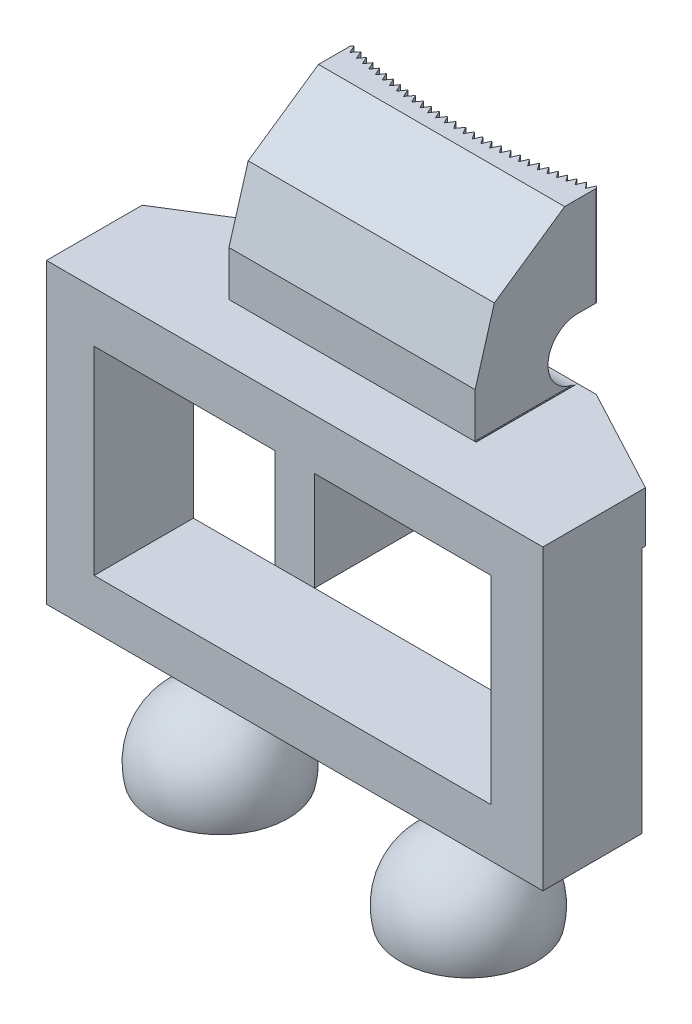
SolidWorks part; units mm, degrees
ref_plane "Front Plane" through (0, 0, 0) normal (0, 0, 1) x (1, 0, 0)
ref_plane "Top Plane" through (0, 0, 0) normal (0, 1, 0) x (1, 0, 0)
ref_plane "Right Plane" through (0, 0, 0) normal (1, 0, 0) x (0, 0, -1)
sketch "Sketch1" plane through (0, 0, 0) normal (0, 0, 1) x (1, 0, 0)
  line L5 (0, 0) -> (20, 0)
  line L6 (0, 0) -> (0, 10)
  line L7 (0, 10) -> (20, 10)
  line L8 (20, 0) -> (20, 10)
  line L9 (-2.3985, 12.5459) -> (22.6015, 12.5459)
  line L10 (-2.3985, 12.5459) -> (-2.3985, -2.4541)
  line L11 (-2.3985, -2.4541) -> (22.6015, -2.4541)
  line L12 (22.6015, 12.5459) -> (22.6015, -2.4541)
  dimension "D1" = 10
  dimension "D2" = 20
  dimension "D3" = 15
  dimension "D4" = 25
extrude "Boss-Extrude1" add sketch "Sketch1" along normal blind 5
sketch "Sketch2" plane through (0, -2.4541, 0) normal (0, -1, 0) x (1, 0, 0)
  line L3 (10.1015, 2.5) -> (10.1015, 0)
  line L4 (-2.3985, 0) -> (22.6015, 0) construction
  circle A0 centre (16.3515, 2.5) radius 0.5
  circle A1 centre (3.8515, 2.5) radius 0.5
  dimension "D1" = 1
extrude "Boss-Extrude2" add sketch "Sketch2" along normal blind 2 contours A1 | A0
ref_plane "Plane1" through (3.8515, 0, 0) normal (-1, 0, 0) x (0, 0, 1)
sketch "Sketch4" plane through (3.8515, 0, 0) normal (-1, 0, 0) x (0, 0, 1)
  line L1 (2, -4.4541) -> (3, -4.4541) construction
  line L2 (2.5, -4.4541) -> (2.5, -3.9541)
  line L4 (-0.4312, -8.0929) -> (-0.9159, -8.2167)
  arc A0 (2.5, -4.4541) -> (-0.4312, -8.0929) centre (2.5, -7.4541) ccw
  arc A1 (2.5, -3.9541) -> (-0.9159, -8.2167) centre (2.5, -7.4541) ccw
  dimension "D2" = 7
  dimension "D1" = 3
revolve "Revolve1" add sketch "Sketch4" angle 360 about L2
ref_plane "Plane2" through (10.1015, 0, 0) normal (-1, 0, 0) x (0, 0, 1)
mirror "Mirror1" about plane through (10.1015, 0, 0) normal (-1, 0, 0) of "Revolve1"
sketch "Sketch5" plane through (0, 10, 0) normal (0, -1, 0) x (1, 0, 0)
  line L9 (11.1015, 0) -> (11.1015, 5)
  line L10 (9.1015, 0) -> (9.1015, 5)
  line L11 (11.1015, 0) -> (9.1015, 0)
  line L12 (11.1015, 5) -> (9.1015, 5)
extrude "Boss-Extrude3" add sketch "Sketch5" along normal blind 5
sketch "Sketch6" plane through (0, 12.5459, 0) normal (0, 1, 0) x (1, 0, 0)
  line L0 (10.1015, 0) -> (10.1015, -5)
  line L1 (22.6015, 0) -> (-2.3985, 0) construction
  line L2 (22.6015, -5) -> (-2.3985, -5) construction
sketch "Sketch9" plane through (0, 12.5459, 0) normal (0, 1, 0) x (1, 0, 0)
  line L0 (22.6015, 0) -> (22.6015, 3)
  line L1 (22.6015, 3) -> (-2.3985, 3)
  line L2 (-2.3985, 3) -> (-2.3985, 0)
  line L3 (22.6015, 0) -> (-2.3985, 0)
  dimension "D1" = 3
  dimension "D2" = 25
extrude "Boss-Extrude6" add sketch "Sketch9" against normal blind 2.5458 contours L1 L2 L3 L0
sketch "Sketch10" plane through (-2.3985, 0, 0) normal (-1, 0, 0) x (0, 0, 1)
  line L3 (-3, 20.5459) -> (-3, 15.5459)
  line L4 (-3, 20.5459) -> (-3, 15.5459)
  line L5 (-3, 12.5459) -> (2.1099, 12.5459)
  line L6 (-3, 20.5459) -> (-2.3985, 20.5459)
  line L7 (-2.3985, 20.5459) -> (1.1419, 18.1122)
  line L9 (1.1419, 18.1122) -> (2.1099, 14.8124)
  line L10 (2.1099, 14.8124) -> (2.1099, 12.5459)
  arc A0 (-3, 12.5459) -> (-3, 15.5459) centre (-3.0614, 14.0459) ccw
  circle A1 centre (-2.1099, 12.5459) radius 12.9256
  dimension "D3" = 5
extrude "Boss-Extrude11" add sketch "Sketch10" against normal blind 25 contours L3 L6 L7 L9 L10 L5 A0
sketch "Sketch11" plane through (0, 20.5459, 0) normal (0, 1, 0) x (1, 0, 0)
  line L1 (22.6015, 6.37) -> (22.2185, 6.5835)
  line L2 (10.3551, 3.3672) -> (10.1015, 3.0172)
  line L5 (22.2065, 6.1451) -> (22.2185, 6.5835)
  line L6 (22.2065, 6.1451) -> (21.8398, 6.3643)
  line L7 (21.8398, 6.3643) -> (21.8398, 5.9448)
  line L8 (21.8398, 5.9448) -> (21.4709, 6.1653)
  line L9 (21.4709, 6.1653) -> (21.4709, 5.7513)
  line L10 (21.4709, 5.7513) -> (21.0903, 5.9787)
  line L11 (21.0903, 5.9787) -> (21.0903, 5.5597)
  line L12 (21.0903, 5.5597) -> (20.715, 5.784)
  line L13 (20.715, 5.784) -> (20.715, 5.3787)
  line L14 (20.715, 5.3787) -> (20.3402, 5.6027)
  line L15 (20.3402, 5.6027) -> (20.3402, 5.2056)
  line L16 (20.3402, 5.2056) -> (19.9698, 5.427)
  line L17 (19.9698, 5.427) -> (19.9698, 5.0419)
  line L18 (19.9698, 5.0419) -> (19.6095, 5.2572)
  line L19 (19.6095, 5.2572) -> (19.6095, 4.8895)
  line L20 (19.6095, 4.8895) -> (19.24, 5.1102)
  line L21 (19.24, 5.1102) -> (19.204, 4.7258)
  line L22 (19.204, 4.7258) -> (18.8434, 4.9413)
  line L23 (18.8434, 4.9413) -> (18.809, 4.5743)
  line L24 (18.809, 4.5743) -> (18.4829, 4.8336)
  line L25 (18.4829, 4.8336) -> (18.4343, 4.4377)
  line L26 (18.4343, 4.4377) -> (18.0993, 4.704)
  line L27 (18.0993, 4.704) -> (18.0296, 4.2976)
  line L28 (18.0296, 4.2976) -> (17.6859, 4.5708)
  line L29 (17.6859, 4.5708) -> (17.6366, 4.1691)
  line L30 (10.7776, 3.3845) -> (10.5576, 3.0172)
  line L31 (17.3643, 4.4686) -> (17.6366, 4.1691)
  line L32 (17.2415, 4.0471) -> (17.3643, 4.4686)
  line L33 (16.9499, 4.3385) -> (17.2415, 4.0471)
  line L34 (16.8302, 3.9276) -> (16.9499, 4.3385)
  line L35 (16.5619, 4.2228) -> (16.8302, 3.9276)
  line L36 (16.4454, 3.8228) -> (16.5619, 4.2228)
  line L37 (16.2053, 4.1025) -> (16.4454, 3.8228)
  line L38 (16.0354, 3.7184) -> (16.2053, 4.1025)
  line L39 (15.784, 4.0114) -> (16.0354, 3.7184)
  line L40 (15.6099, 3.6178) -> (15.784, 4.0114)
  line L41 (15.3975, 3.918) -> (15.6099, 3.6178)
  line L42 (15.2278, 3.5341) -> (15.3975, 3.918)
  line L43 (15.0053, 3.8485) -> (15.2278, 3.5341)
  line L44 (14.8308, 3.4538) -> (15.0053, 3.8485)
  line L45 (14.6014, 3.778) -> (14.8308, 3.4538)
  line L46 (14.4248, 3.3787) -> (14.6014, 3.778)
  line L47 (14.1908, 3.7095) -> (14.4248, 3.3787)
  line L48 (14.014, 3.3097) -> (14.1908, 3.7095)
  line L49 (13.772, 3.6518) -> (14.014, 3.3097)
  line L50 (13.5926, 3.2463) -> (13.772, 3.6518)
  line L51 (13.3535, 3.5843) -> (13.5926, 3.2463)
  line L52 (13.1797, 3.1912) -> (13.3535, 3.5843)
  line L53 (12.9374, 3.5337) -> (13.1797, 3.1912)
  line L54 (12.7646, 3.143) -> (12.9374, 3.5337)
  line L55 (12.7646, 3.143) -> (12.5017, 3.4939)
  line L56 (9.8479, 3.3672) -> (9.6181, 3.0172)
  line L57 (12.3122, 3.0985) -> (12.5017, 3.4939)
  line L58 (9.6181, 3.0172) -> (9.4255, 3.3845)
  line L59 (12.3122, 3.0985) -> (12.0558, 3.4541)
  line L60 (9.1771, 3.0172) -> (9.4255, 3.3845)
  line L61 (11.8591, 3.0622) -> (12.0558, 3.4541)
  line L62 (11.8591, 3.0622) -> (11.6199, 3.4161)
  line L63 (11.6199, 3.4161) -> (11.4421, 3.0362)
  line L64 (11.4421, 3.0362) -> (11.2014, 3.3922)
  line L65 (11.2014, 3.3922) -> (11.0259, 3.0172)
  line L66 (11.0259, 3.0172) -> (10.7776, 3.3845)
  line L67 (10.5576, 3.0172) -> (10.3551, 3.3672)
  line L68 (9.8479, 3.3672) -> (10.1015, 3.0172)
  line L69 (22.6015, 6.37) -> (22.6015, 3)
  line L70 (22.6015, 3) -> (-2.3985, 3)
  line L71 (10.1015, 2.75) -> (10.1015, -2.75) construction
  line L72 (9.0017, 3.3922) -> (9.1771, 3.0172)
  line L73 (8.761, 3.0362) -> (9.0017, 3.3922)
  line L74 (8.5832, 3.4161) -> (8.761, 3.0362)
  line L75 (8.3439, 3.0622) -> (8.5832, 3.4161)
  line L76 (8.3439, 3.0622) -> (8.1473, 3.4541)
  line L77 (7.8908, 3.0985) -> (8.1473, 3.4541)
  line L78 (7.8908, 3.0985) -> (7.7014, 3.4939)
  line L79 (7.4385, 3.143) -> (7.7014, 3.4939)
  line L80 (7.4385, 3.143) -> (7.2657, 3.5337)
  line L81 (7.2657, 3.5337) -> (7.0234, 3.1912)
  line L82 (7.0234, 3.1912) -> (6.8496, 3.5843)
  line L83 (6.8496, 3.5843) -> (6.6105, 3.2463)
  line L84 (6.6105, 3.2463) -> (6.4311, 3.6518)
  line L85 (6.4311, 3.6518) -> (6.1891, 3.3097)
  line L86 (6.1891, 3.3097) -> (6.0123, 3.7095)
  line L87 (6.0123, 3.7095) -> (5.7782, 3.3787)
  line L88 (5.7782, 3.3787) -> (5.6016, 3.778)
  line L89 (5.6016, 3.778) -> (5.3723, 3.4538)
  line L90 (5.3723, 3.4538) -> (5.1977, 3.8485)
  line L91 (5.1977, 3.8485) -> (4.9753, 3.5341)
  line L92 (4.9753, 3.5341) -> (4.8055, 3.918)
  line L93 (4.8055, 3.918) -> (4.5931, 3.6178)
  line L94 (4.5931, 3.6178) -> (4.419, 4.0114)
  line L95 (4.419, 4.0114) -> (4.1676, 3.7184)
  line L96 (4.1676, 3.7184) -> (3.9977, 4.1025)
  line L97 (3.9977, 4.1025) -> (3.7577, 3.8228)
  line L98 (3.7577, 3.8228) -> (3.6412, 4.2228)
  line L99 (3.6412, 4.2228) -> (3.3728, 3.9276)
  line L100 (3.3728, 3.9276) -> (3.2531, 4.3385)
  line L101 (3.2531, 4.3385) -> (2.9615, 4.0471)
  line L102 (2.9615, 4.0471) -> (2.8387, 4.4686)
  line L103 (2.8387, 4.4686) -> (2.5665, 4.1691)
  line L104 (2.5172, 4.5708) -> (2.5665, 4.1691)
  line L105 (2.1735, 4.2976) -> (2.5172, 4.5708)
  line L106 (2.1038, 4.704) -> (2.1735, 4.2976)
  line L107 (1.7687, 4.4377) -> (2.1038, 4.704)
  line L108 (1.7202, 4.8336) -> (1.7687, 4.4377)
  line L109 (1.394, 4.5743) -> (1.7202, 4.8336)
  line L110 (1.3596, 4.9413) -> (1.394, 4.5743)
  line L111 (0.999, 4.7258) -> (1.3596, 4.9413)
  line L112 (0.963, 5.1102) -> (0.999, 4.7258)
  line L113 (0.5936, 4.8895) -> (0.963, 5.1102)
  line L114 (0.5936, 5.2572) -> (0.5936, 4.8895)
  line L115 (0.2333, 5.0419) -> (0.5936, 5.2572)
  line L116 (0.2333, 5.427) -> (0.2333, 5.0419)
  line L117 (-0.1372, 5.2056) -> (0.2333, 5.427)
  line L118 (-0.1372, 5.6027) -> (-0.1372, 5.2056)
  line L119 (-0.512, 5.3787) -> (-0.1372, 5.6027)
  line L120 (-0.512, 5.784) -> (-0.512, 5.3787)
  line L121 (-0.8872, 5.5597) -> (-0.512, 5.784)
  line L122 (-0.8872, 5.9787) -> (-0.8872, 5.5597)
  line L123 (-1.2679, 5.7513) -> (-0.8872, 5.9787)
  line L124 (-1.2679, 6.1653) -> (-1.2679, 5.7513)
  line L125 (-1.6368, 5.9448) -> (-1.2679, 6.1653)
  line L126 (-1.6368, 6.3643) -> (-1.6368, 5.9448)
  line L127 (-2.0035, 6.1451) -> (-1.6368, 6.3643)
  line L128 (-2.0035, 6.1451) -> (-2.0154, 6.5835)
  line L130 (-2.3985, 6.37) -> (-2.0154, 6.5835)
  line L131 (-2.3985, 3) -> (-2.3985, 6.37)
extrude "Boss-Extrude12" add sketch "Sketch11" against normal blind 5 contours L117 L116 L115 L114 L113 L112 L111 L110 L109 L108 L107 L106 L105 L104 L103 L102 L101 L100 L99 L98 L97 L96 L95 L94 L93 L92 L91 L90 L89 L88 L87 L86 L85 L84 L83 L82 L81 L80 L79 L78 L77 L76 L75 L74 L73 L72 L60 L58 L56 L68 L2 L67 L30 L66 L65 L64 L63 L62 L61 L59 L57 L55 L54 L53 L52 L51 L50 L49 L48 L47 L46 L45 L44 L43 L42 L41 L40 L39 L38 L37 L36 L35 L34 L33 L32 L31 L29 L28 L27 L26 L25 L24 L23 L22 L21 L20 L19 L18 L17 L16 L15 L14 L13 L12 L11 L10 L9 L8 L7 L6 L5 L1 L69 L70 L131 L130 L128 L127 L126 L125 L124 L123 L122 L121 L120 L119 L118
sketch "Sketch13" plane through (-2.3985, 0, 0) normal (-1, 0, 0) x (0, 0, 1)
  line L1 (-7.6191, 21.1571) -> (8.0532, 21.1571)
  line L2 (-7.6191, 21.1571) -> (-7.6191, 12.5459)
  line L3 (-7.6191, 12.5459) -> (8.0532, 12.5459)
  line L4 (8.0532, 21.1571) -> (8.0532, 12.5459)
extrude "Cut-Extrude2" cut sketch "Sketch13" against normal blind 6.3 contours L1 L4 L3 L2
sketch "Sketch14" plane through (22.6015, 0, 0) normal (1, 0, 0) x (0, 0, -1)
  line L1 (-8.117, 12.5667) -> (7.8568, 12.5667)
  line L2 (-8.117, 12.5667) -> (-8.117, 21.0354)
  line L3 (-8.117, 21.0354) -> (7.8568, 21.0354)
  line L4 (7.8568, 12.5667) -> (7.8568, 21.0354)
extrude "Cut-Extrude4" cut sketch "Sketch14" against normal blind 6.3 contours L2 L3 L4 L1
sketch "Sketch17" plane through (22.6015, 0, 0) normal (1, 0, 0) x (0, 0, -1)
  line L0 (-2.1099, 12.5667) -> (-2.1099, 12.5459)
  line L1 (-2.1099, 12.5459) -> (3, 12.5459)
  line L2 (3, 12.5459) -> (3, 12.5667)
  line L3 (3, 12.5667) -> (-2.1099, 12.5667)
extrude "Cut-Extrude6" cut sketch "Sketch17" against normal blind 6.25
sketch "Sketch21" plane through (0, 12.5459, 0) normal (0, 1, 0) x (1, 0, 0)
  line L13 (-2.3985, -0.181) -> (-2.3985, 3)
  line L14 (-2.3985, 3) -> (2.7051, 3)
  line L15 (17.2949, 3) -> (22.6015, 3)
  line L16 (22.6015, 3) -> (22.6015, 0.1707)
  line L17 (22.6015, 0.1707) -> (17.2949, 3)
  line L18 (2.7051, 3) -> (-2.3985, -0.181)
extrude "Cut-Extrude9" cut sketch "Sketch21" against normal blind 2.75
ref_plane "Plane4" through (0, 0, 2.5) normal (0, 0, 1) x (1, 0, 0)
